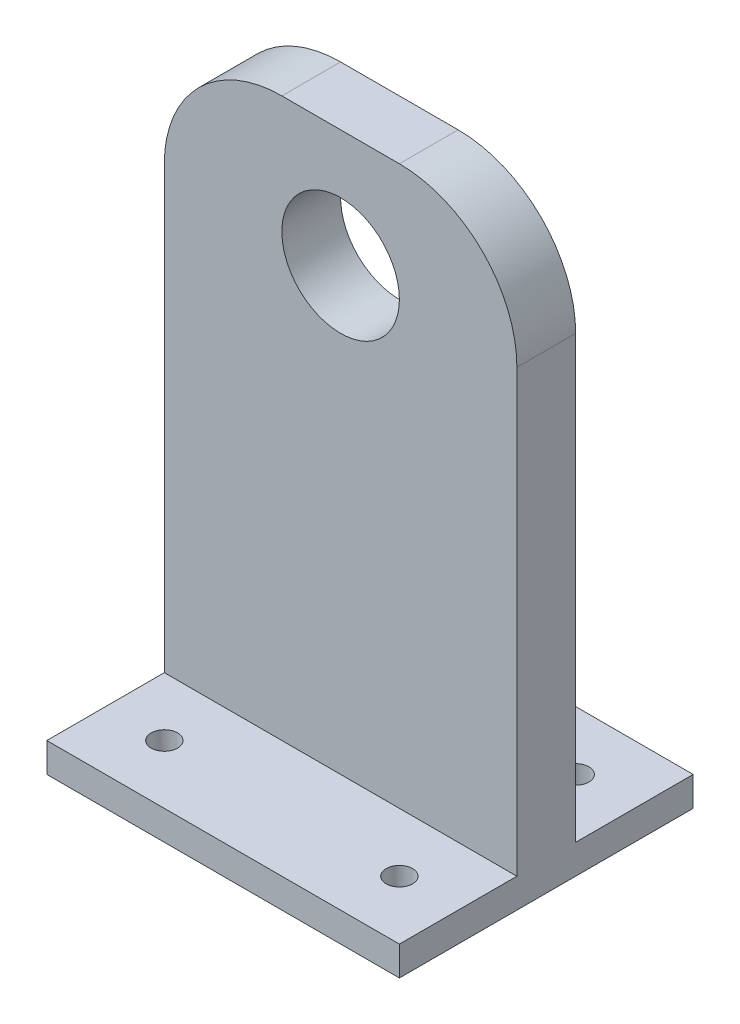
SolidWorks part; units mm, degrees
ref_plane "前视基准面" through (0, 0, 0) normal (0, 0, 1) x (1, 0, 0)
ref_plane "上视基准面" through (0, 0, 0) normal (0, 1, 0) x (1, 0, 0)
ref_plane "右视基准面" through (0, 0, 0) normal (1, 0, 0) x (0, 0, -1)
sketch "草图1" plane through (0, 0, 0) normal (0, 0, 1) x (1, 0, 0)
  line L0 (0, 100) -> (0, 0) construction
  line L2 (-30, 100) -> (30, 100)
  line L3 (-30, 100) -> (-30, 0)
  line L4 (-30, 0) -> (30, 0)
  line L5 (30, 100) -> (30, 0)
  circle A0 centre (0, 80) radius 10
  dimension "D4" = 20
  dimension "D1" = 100
  dimension "D2" = 60
  dimension "D3" = 30
  dimension "D5" = 80
  dimension "D6" = 100
extrude "凸台-拉伸1" add sketch "草图1" along normal blind 10
sketch "草图2" plane through (0, 0, 0) normal (0, 0, -1) x (-1, 0, 0)
  circle A0 centre (0, 80) radius 10
extrude "凸台-拉伸2" add sketch "草图2" against normal blind 2
fillet "圆角1" radius 20 2 edges at (30, 100, 5) (-30, 100, 5)
sketch "草图3" plane through (0, 0, 0) normal (0, -1, 0) x (1, 0, 0)
  line L0 (-40.659, 5) -> (46.5829, 5) construction
  line L5 (30, 10) -> (30, 0) construction
  line L6 (-30, 30) -> (30, 30)
  line L7 (-30, 30) -> (-30, -20)
  line L8 (-30, -20) -> (30, -20)
  line L9 (30, 30) -> (30, -20)
  line L10 (-30, 10) -> (-30, 0) construction
  dimension "D1" = 50
  dimension "D2" = 25
extrude "凸台-拉伸3" add sketch "草图3" against normal blind 5
sketch "草图4" plane through (0, 5, 0) normal (0, 1, 0) x (1, 0, 0)
  line L0 (0, 26.898) -> (0, -45.0743) construction
  line L1 (-30, 10) -> (30, 10) construction
  line L2 (-30, 0) -> (-30, 20) construction
  line L3 (30, 20) -> (30, 0) construction
  line L4 (30, -20) -> (-30, -20) construction
  line L5 (30, -10) -> (30, -30) construction
  line L6 (-30, -30) -> (-30, -10) construction
  circle A0 centre (-20, 10) radius 2.25
  circle A1 centre (20, 10) radius 2.25
  circle A2 centre (-20, -20) radius 2.25
  circle A3 centre (20, -20) radius 2.25
  dimension "D1" = 4.5
  dimension "D2" = 4.5
  dimension "D3" = 4.5
  dimension "D4" = 4.5
  dimension "D5" = 20
  dimension "D6" = 20
  dimension "D7" = 20
  dimension "D8" = 20
extrude "切除-拉伸1" cut sketch "草图4" against normal through all
sketch "草图5" plane through (0, 0, 2) normal (0, 0, 1) x (1, 0, 0)
  circle A0 centre (0, 80) radius 10
extrude "切除-拉伸2" cut sketch "草图5" against normal blind 10
